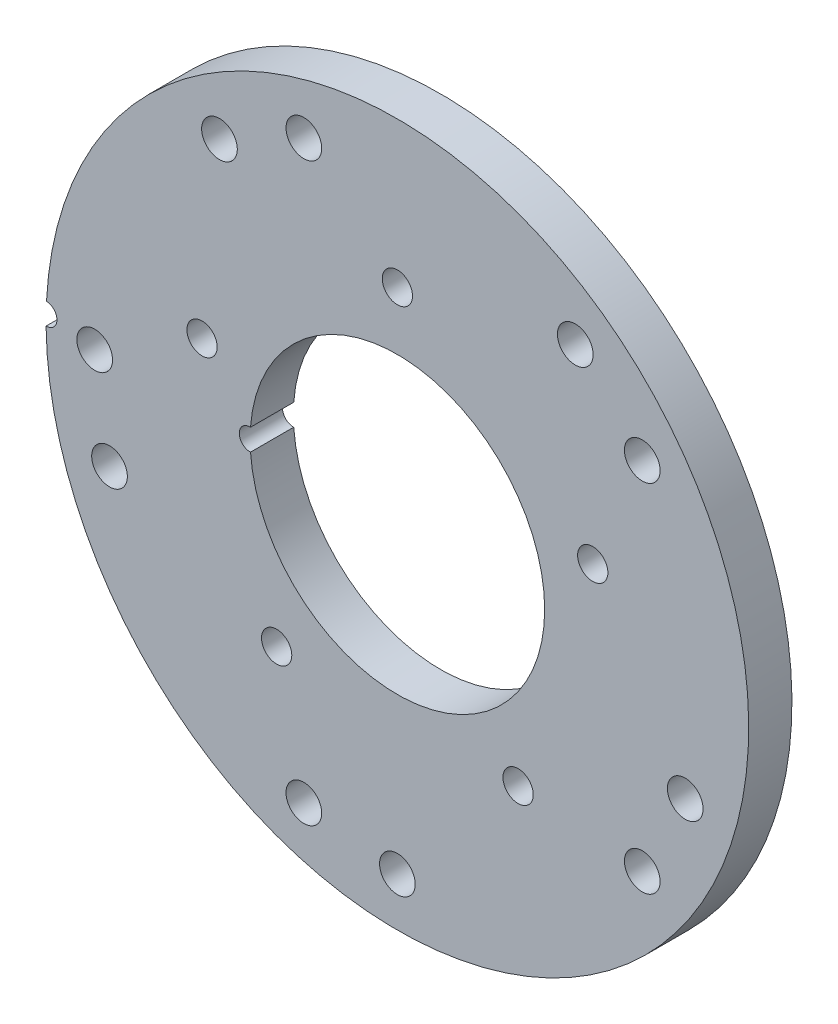
SolidWorks part; units mm, degrees
other "标注1"
sketch "草图3" plane through (-32.7458, -31.847, 4) normal (-0.4852, -0.3872, 0.784) x (0.7539, -0.6395, 0.1507)
ref_plane "前视基准面" through (0, 0, 0) normal (0, 0, 1) x (1, 0, 0)
ref_plane "上视基准面" through (0, 0, 0) normal (0, 1, 0) x (1, 0, 0)
ref_plane "右视基准面" through (0, 0, 0) normal (1, 0, 0) x (0, 0, -1)
sketch "草图1" plane through (0, 0, 0) normal (0, 0, 1) x (1, 0, 0)
  line L0 (-26.6296, -8.6525) -> (0, -28) construction
  line L1 (-13.3148, -18.3262) -> (-4.9931, -6.8724) construction
  line L2 (0, 0) -> (0, -52.0706) construction
  line L3 (0, 0) -> (-17.6382, -54.2848) construction
  circle A0 centre (0, 0) radius 32.5
  circle A1 centre (0, 0) radius 13.625
  circle A2 centre (0, -28) radius 1.65
  circle A3 centre (-26.6296, -8.6525) radius 1.65
  circle A4 centre (-16.458, 22.6525) radius 1.65
  circle A5 centre (16.458, 22.6525) radius 1.65
  circle A6 centre (26.6296, -8.6525) radius 1.65
  circle A7 centre (0, 0) radius 19 construction
  circle A8 centre (-11.1679, -15.3713) radius 1.4
  circle A9 centre (-18.0701, 5.8713) radius 1.4
  circle A10 centre (0, 19) radius 1.4
  circle A11 centre (18.0701, 5.8713) radius 1.4
  circle A12 centre (11.1679, -15.3713) radius 1.4
  circle A13 centre (0, 0) radius 28 construction
  circle A14 centre (-8.6525, -26.6296) radius 1.65
  circle A15 centre (8.6525, -26.6296) radius 1.65 construction
  circle A16 centre (-28, 0) radius 1.65
  circle A17 centre (-22.6525, -16.458) radius 1.65 construction
  circle A18 centre (-8.6525, 26.6296) radius 1.65
  circle A19 centre (-22.6525, 16.458) radius 1.65 construction
  circle A20 centre (22.6525, 16.458) radius 1.65
  circle A21 centre (8.6525, 26.6296) radius 1.65 construction
  circle A22 centre (22.6525, -16.458) radius 1.65
  circle A23 centre (28, 0) radius 1.65 construction
  dimension "D1" = 65
  dimension "D2" = 38
  dimension "D3" = 27.25
  dimension "D4" = 2.8
  dimension "D6" = 18
  dimension "D7" = 3.3
  dimension "D5" = 5
  dimension "D8" = 5
extrude "凸台-拉伸1" add sketch "草图1" along normal blind 4 contours A0
sketch "草图2" plane through (0, 0, 4) normal (0, 0, 1) x (1, 0, 0)
  circle A0 centre (-13.625, 0) radius 1
  circle A1 centre (0, 0) radius 13.625 construction
  circle A2 centre (-32.4935, 0.6476) radius 1
  circle A3 centre (0, 0) radius 32.5 construction
extrude "切除-拉伸1" cut sketch "草图2" against normal blind 10
